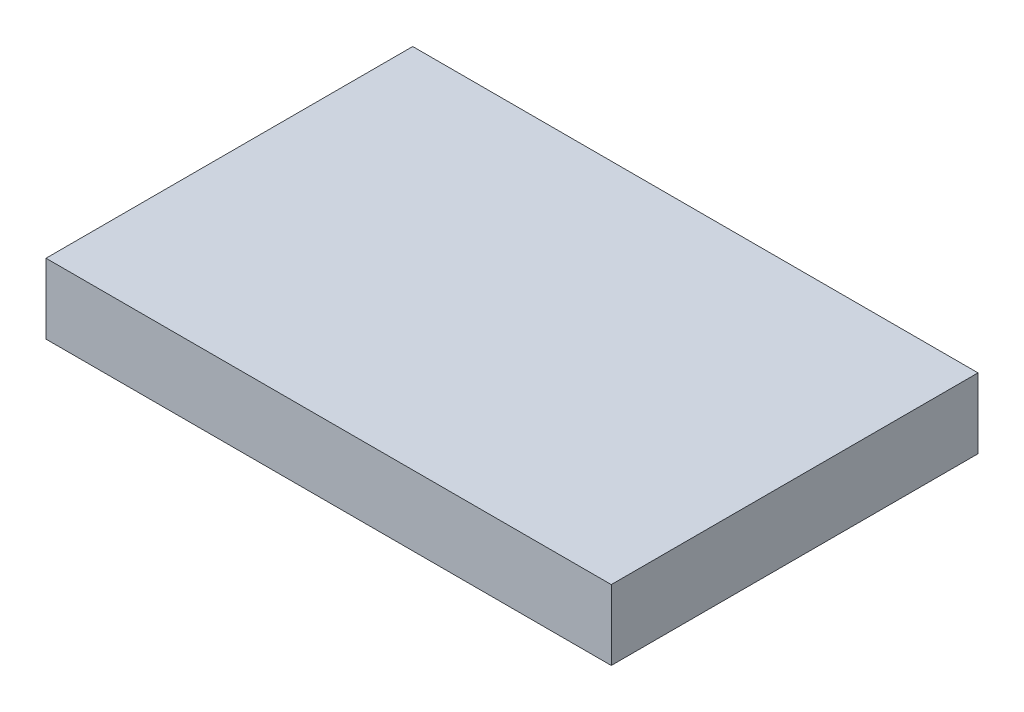
SolidWorks part; units mm, degrees
ref_plane "Front Plane" through (0, 0, 0) normal (0, 0, 1) x (1, 0, 0)
ref_plane "Top Plane" through (0, 0, 0) normal (0, 1, 0) x (1, 0, 0)
ref_plane "Right Plane" through (0, 0, 0) normal (1, 0, 0) x (0, 0, -1)
sketch "Sketch1" plane through (0, 0, 0) normal (0, 1, 0) x (1, 0, 0)
  line L1 (16.7, 343.2577) -> (631.38, 343.2577)
  line L2 (16.7, 343.2577) -> (16.7, -55.5223)
  line L3 (16.7, -55.5223) -> (631.38, -55.5223)
  line L4 (631.38, 343.2577) -> (631.38, -55.5223)
extrude "Boss-Extrude2" add sketch "Sketch1" along normal blind 76.2
